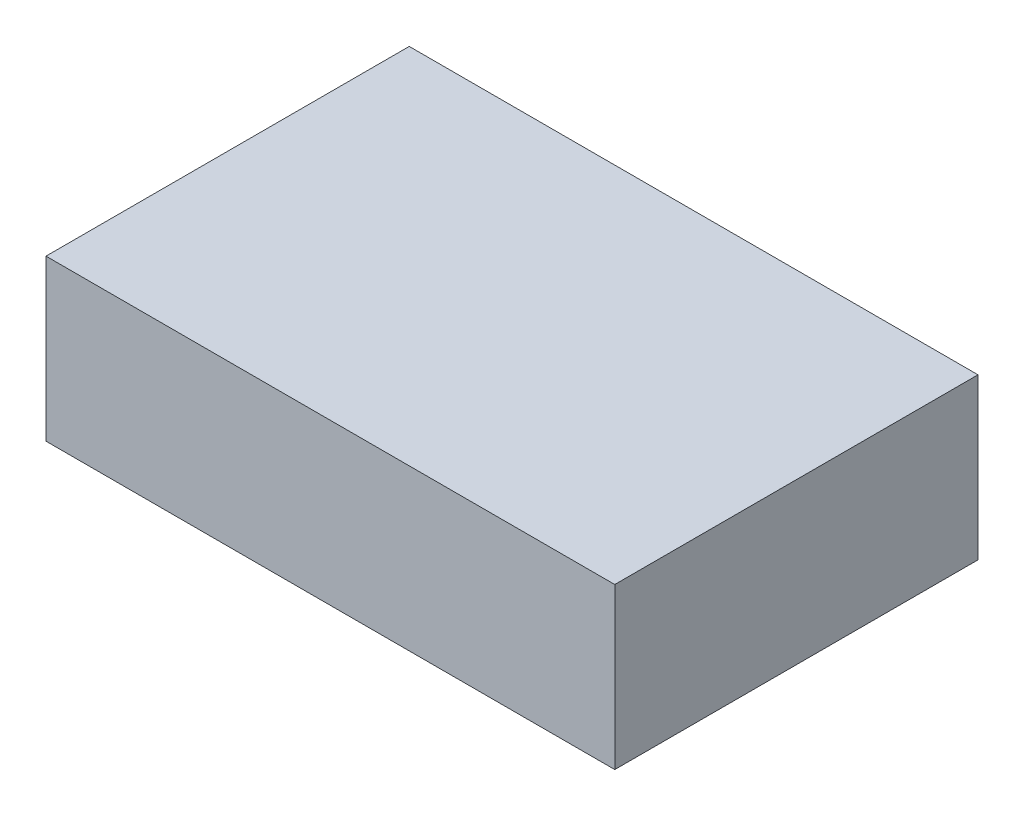
SolidWorks part; units mm, degrees
ref_plane "Přední rovina" through (0, 0, 0) normal (0, 0, 1) x (1, 0, 0)
ref_plane "Vrchní rovina" through (0, 0, 0) normal (0, 1, 0) x (1, 0, 0)
ref_plane "Pravá rovina" through (0, 0, 0) normal (1, 0, 0) x (0, 0, -1)
sketch "Skica1" plane through (0, 0, 0) normal (0, 1, 0) x (1, 0, 0)
  line L1 (0, 0) -> (88, 0)
  line L2 (0, 0) -> (0, 56.2)
  line L3 (0, 56.2) -> (88, 56.2)
  line L4 (88, 0) -> (88, 56.2)
  dimension "D1" = 88
  dimension "D2" = 56.2
extrude "Přidat vysunutím1" add sketch "Skica1" along normal blind 24.8
